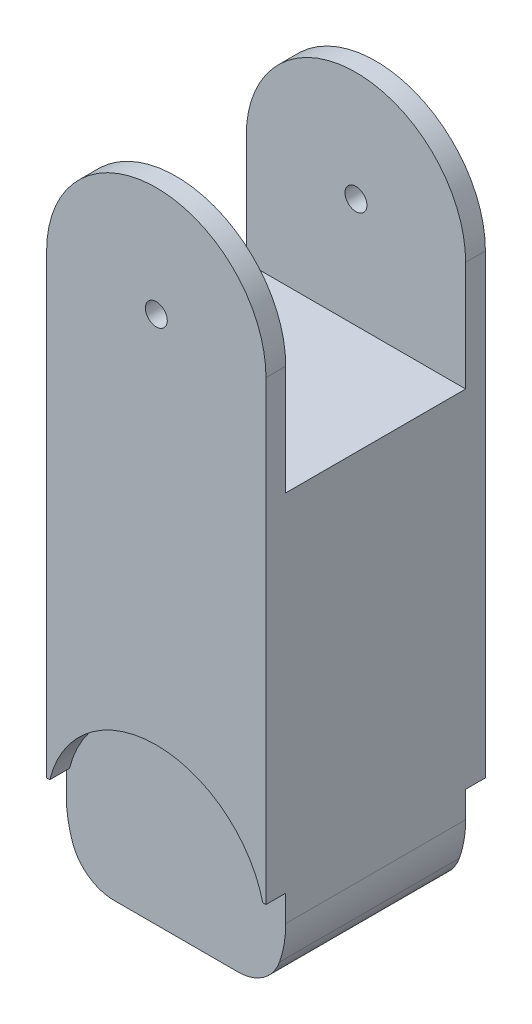
SolidWorks part; units mm, degrees
ref_plane "Front Plane" through (0, 0, 0) normal (0, 0, 1) x (1, 0, 0)
ref_plane "Top Plane" through (0, 0, 0) normal (0, 1, 0) x (1, 0, 0)
ref_plane "Right Plane" through (0, 0, 0) normal (1, 0, 0) x (0, 0, -1)
sketch "Sketch1" plane through (0, 0, 0) normal (0, 1, 0) x (1, 0, 0)
  line L1 (-25, -25) -> (25, -25)
  line L2 (-25, -25) -> (-25, 25)
  line L3 (-25, 25) -> (25, 25)
  line L4 (25, -25) -> (25, 25)
  line L5 (-25, -25) -> (25, 25) construction
  line L6 (-25, 25) -> (25, -25) construction
  point P0 (0, 0)
  dimension "D1" = 50
  dimension "D2" = 50
extrude "Boss-Extrude1" add sketch "Sketch1" along normal blind 100
sketch "Sketch2" plane through (0, 0, 25) normal (0, 0, 1) x (1, 0, 0)
  line L1 (25, 100) -> (25, 0) construction
  line L2 (27.5, 0) -> (-27.5, 0) construction
  line L4 (-25, 0) -> (25, 0)
  line L6 (-25, 21) -> (-24.2693, 21)
  line L7 (0, -27.5) -> (0, 27.5) construction
  line L8 (-25, 0) -> (-25, 21)
  line L9 (-25, 100) -> (-25, 0) construction
  line L10 (25, 21) -> (25, 0)
  line L11 (24.2693, 21) -> (25, 21)
  line L12 (25, 100) -> (25, 0) construction
  arc A0 (-24.2693, 21) -> (24.2693, 21) centre (0, 15) cw
  arc A1 (25, 15.6717) -> (-25, 15.6717) centre (0, 15) ccw construction
  dimension "D1" = 0.7307
extrude "Cut-Extrude1" cut sketch "Sketch2" against normal blind 4.5
mirror "Mirror1" about plane through (0, 0, 0) normal (0, 0, 1) of "Cut-Extrude1"
sketch "Sketch4" plane through (0, 0, -25) normal (0, 0, -1) x (-1, 0, 0)
  line L0 (25, 100) -> (25, 21) construction
  line L1 (-25, 100) -> (25, 100)
  line L2 (-25, 100) -> (-25, 125)
  line L4 (25, 100) -> (25, 125)
  arc A0 (-25, 125) -> (25, 125) centre (0, 125) cw
  circle A1 centre (0, 125) radius 2.5
  dimension "D2" = 5
  dimension "D1" = 25
extrude "Boss-Extrude2" add sketch "Sketch4" against normal blind 4.5
mirror "Mirror2" about plane through (0, 0, 0) normal (0, 0, 1) of "Boss-Extrude2"
sketch "Sketch5" plane through (0, 0, -20.5) normal (0, 0, -1) x (-1, 0, 0)
  line L0 (-25, 15) -> (-25, -11.7161)
  line L1 (-25, -11.7161) -> (25, -11.7161)
  line L2 (25, -11.7161) -> (25, 15)
  arc A0 (-25, 15) -> (25, 15) centre (0, 15) ccw
extrude "Cut-Extrude2" cut sketch "Sketch5" against normal through all both and the other way through all
fillet "Fillet1" radius 10 2 edges at (-20, 0, 0) (20, 0, 0)
